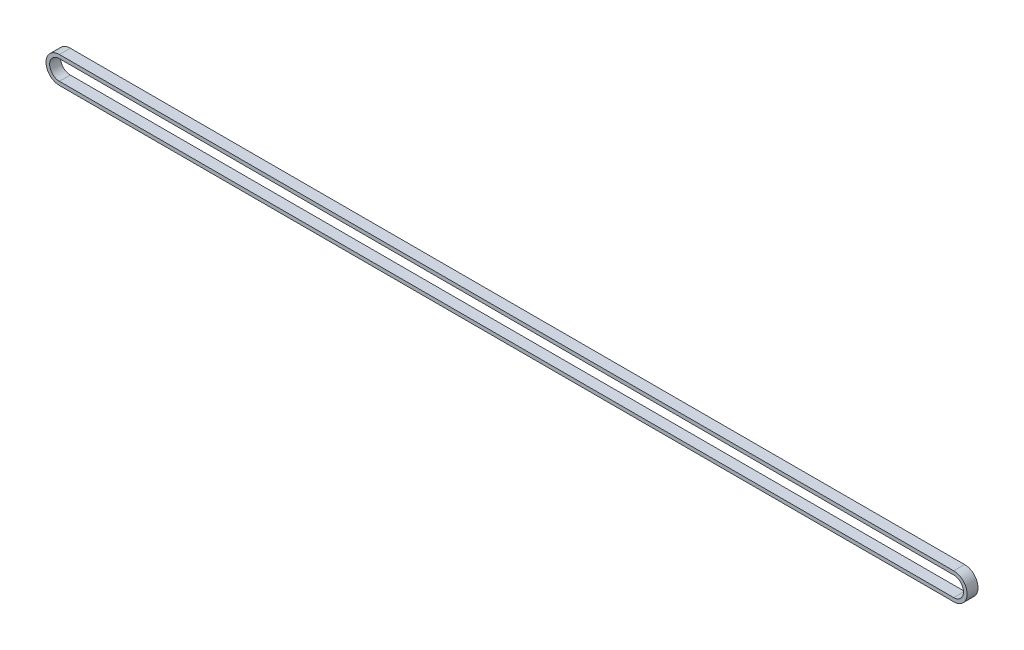
SolidWorks part; units mm, degrees
material "NBR"
ref_plane "Plano frontal" through (0, 0, 0) normal (0, 0, 1) x (1, 0, 0)
ref_plane "Plano superior" through (0, 0, 0) normal (0, 1, 0) x (1, 0, 0)
ref_plane "Plano direito" through (0, 0, 0) normal (1, 0, 0) x (0, 0, -1)
sketch "Esboço1" plane through (0, 0, 0) normal (0, 0, 1) x (1, 0, 0)
  line L0 (-246.5, 0) -> (0, 0) construction
  line L1 (0, 0) -> (0, 11.8238) construction
  line L2 (-246.5, 7.4) -> (246.5, 7.4)
  line L3 (-246.5, 5.4) -> (246.5, 5.4)
  line L4 (-246.5, -5.4) -> (246.5, -5.4)
  line L5 (-246.5, -7.4) -> (246.5, -7.4)
  circle A0 centre (-246.5, 0) radius 5.4
  circle A1 centre (-246.5, 0) radius 7.4
  circle A2 centre (246.5, 0) radius 7.4
  circle A3 centre (246.5, 0) radius 5.4
  point P20 (0, -7.4)
  point P21 (0, -5.4)
  point P22 (0, 5.4)
  point P23 (0, 7.4)
  dimension "D1" = 10.8
  dimension "D2" = 2
  dimension "D3" = 493
extrude "Ressalto-extrusão1" add sketch "Esboço1" along normal mid plane 6 contours L3 A2 L2 A1 | L3 A1 L4 A0 | L5 A2 L4 A1 | L3 A3 L4 A2
